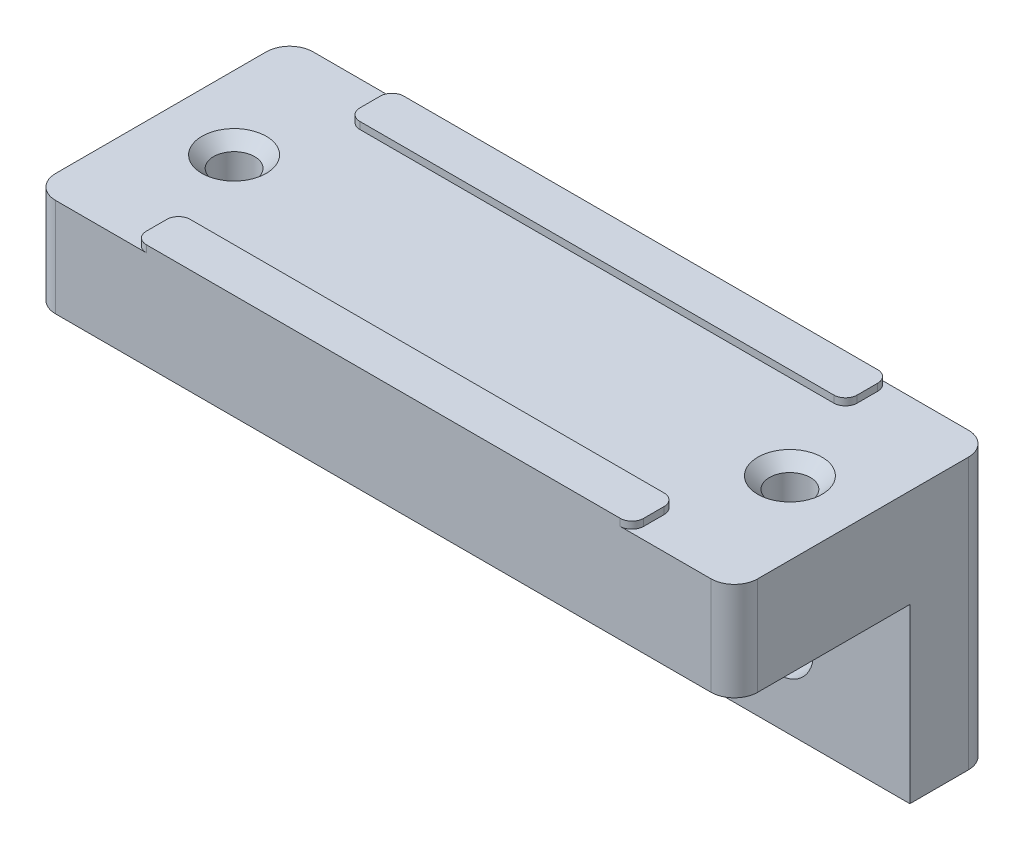
SolidWorks part; units mm, degrees
material "ASTM A36 Steel"
ref_plane "Front Plane" through (0, 0, 0) normal (0, 0, 1) x (1, 0, 0)
ref_plane "Top Plane" through (0, 0, 0) normal (0, 1, 0) x (1, 0, 0)
ref_plane "Right Plane" through (0, 0, 0) normal (1, 0, 0) x (0, 0, -1)
sketch "Sketch1" plane through (0, 0, 0) normal (1, 0, 0) x (0, 0, -1)
  line L0 (5.588, 0) -> (-5.588, 0)
  line L1 (-5.588, -4.572) -> (2.032, -4.572)
  line L2 (5.588, 0) -> (5.588, -12.065)
  line L3 (5.588, -12.065) -> (2.032, -12.065)
  line L4 (-5.588, 0) -> (-5.588, -4.572)
  line L5 (2.032, -4.572) -> (2.032, -12.065)
  dimension "D1" = 4.572
  dimension "D2" = 3.556
  dimension "D3" = 11.176
  dimension "D4" = 12.065
  dimension "D5" = 7.493
extrude "Boss-Extrude1" add sketch "Sketch1" along normal mid plane 30.48
sketch "Sketch7" plane through (0, 0, 0) normal (0, 1, 0) x (1, 0, 0)
  line L0 (-3.0848, 0) -> (-10.8275, 0) construction
  line L1 (10.795, -4.191) -> (10.795, -5.08)
  line L2 (-10.287, 3.683) -> (10.287, 3.683)
  line L3 (-10.795, 4.191) -> (-10.795, 5.08)
  line L4 (-10.287, 5.588) -> (10.287, 5.588)
  line L5 (10.795, 4.191) -> (10.795, 5.08)
  line L6 (-10.287, -5.588) -> (10.287, -5.588)
  line L7 (-10.795, -4.191) -> (-10.795, -5.08)
  line L8 (-10.287, -3.683) -> (10.287, -3.683)
  arc A0 (-10.795, 5.08) -> (-10.287, 5.588) centre (-10.287, 5.08) cw
  arc A1 (-10.287, 3.683) -> (-10.795, 4.191) centre (-10.287, 4.191) cw
  arc A2 (10.287, 3.683) -> (10.795, 4.191) centre (10.287, 4.191) ccw
  arc A3 (10.287, 5.588) -> (10.795, 5.08) centre (10.287, 5.08) cw
  arc A4 (10.287, -5.588) -> (10.795, -5.08) centre (10.287, -5.08) ccw
  arc A5 (10.287, -3.683) -> (10.795, -4.191) centre (10.287, -4.191) cw
  arc A6 (-10.287, -3.683) -> (-10.795, -4.191) centre (-10.287, -4.191) ccw
  arc A7 (-10.795, -5.08) -> (-10.287, -5.588) centre (-10.287, -5.08) ccw
  dimension "D1" = 0.508
  dimension "D2" = 7.366
  dimension "D3" = 21.59
extrude "Cut-Extrude2" cut sketch "Sketch7" against normal blind 0.3048 flip side to cut
hole_wizard "#2-56 Tapped Hole1" positions "Sketch3" profile "Sketch2" tap size "#2-56" standard "Ansi Inch" end condition up to next
sketch "Sketch3" plane through (-6.6564, -0.3048, 7.5004) normal (0, 1, 0) x (-1, 0, 0)
  line L0 (-6.6564, -7.3033) -> (-6.6564, -15.0551) construction
  point P0 (5.4086, -7.5004)
  point P1 (-18.7214, -7.5004)
  dimension "D1" = 24.13
sketch "Sketch2" plane through (-12.065, -0.3048, 0) normal (1, 0, 0) x (0, 0, 1)
  line L0 (0, 0) -> (0, 4.2672)
  line L1 (0, 4.2672) -> (1.397, 4.2672)
  line L2 (0.889, 3.7592) -> (0.889, 0.508)
  line L3 (0.889, 0.508) -> (1.397, 0)
  line L5 (1.397, 0) -> (0, 0)
  line L6 (-0.889, 0.508) -> (-1.397, 0) construction
  line L7 (1.397, 4.2672) -> (0.889, 3.7592)
  line L8 (-1.397, 4.2672) -> (-0.889, 3.7592) construction
  line L11 (0, -6.35) -> (0, 107.95) construction
  dimension "Thread Major Dia." = 1.778
  dimension "Thru Tap Drill Depth" = 4.2672
  dimension "Near C'Sink Dia." = 2.794
  dimension "Near C'Sink Angle" = 90
  dimension "Far C'Sink Dia." = 2.794
  dimension "Far C'Sink Angle" = 90
hole_wizard "#31 (0.12) Diameter Hole1" positions "Sketch6" profile "Sketch5" hole size "#31" standard "Ansi Inch" end condition through all
sketch "Sketch6" plane through (-4.6332, -2.0955, -2.032) normal (0, 0, 1) x (1, 0, 0)
  point P0 (-4.8918, -6.4389)
  point P1 (14.1582, -6.4389)
  dimension "D1" = 3.9624
  dimension "D2" = 9.525
  dimension "D3" = 9.525
sketch "Sketch5" plane through (-9.525, -8.5344, -2.032) normal (1, 0, 0) x (0, -1, 0)
  line L0 (0, 0) -> (0, 3.556)
  line L1 (0, 3.556) -> (1.524, 3.556)
  line L2 (1.524, 3.556) -> (1.524, 0)
  line L5 (1.524, 0) -> (0, 0)
  line L11 (0, -6.35) -> (0, 107.95) construction
  dimension "Thru Hole Dia." = 3.048
  dimension "Thru Hole Depth" = 3.556
fillet "Fillet1" radius 1.016 4 edges at (-15.24, -6.1849, -5.588) (-15.24, -2.4384, 5.588) (15.24, -2.4384, 5.588) (15.24, -6.1849, -5.588)
